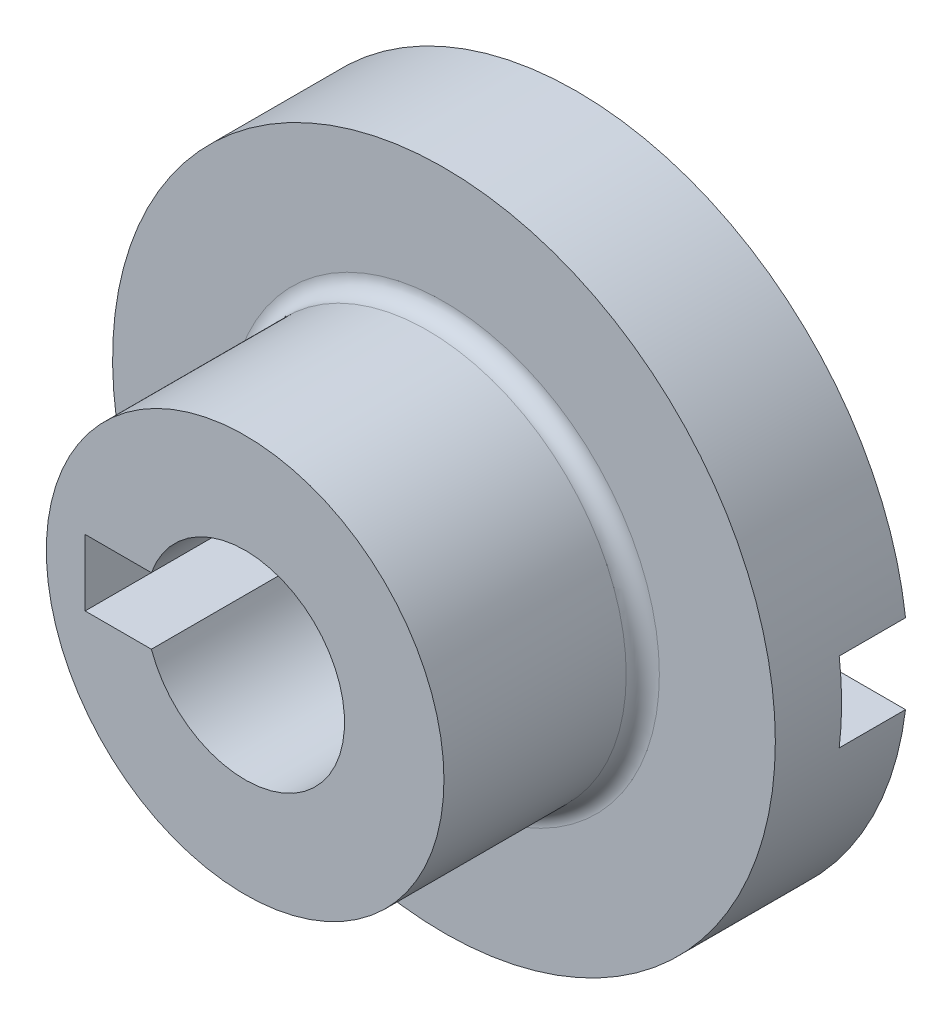
SolidWorks part; units mm, degrees
ref_plane "Front Plane" through (0, 0, 0) normal (0, 0, 1) x (1, 0, 0)
ref_plane "Top Plane" through (0, 0, 0) normal (0, 1, 0) x (1, 0, 0)
ref_plane "Right Plane" through (0, 0, 0) normal (1, 0, 0) x (0, 0, -1)
sketch "Sketch2" plane through (0, 0, 0) normal (0, 0, 1) x (1, 0, 0)
  circle A0 centre (0, 0) radius 50
  dimension "D1" = 100
extrude "Boss-Extrude1" add sketch "Sketch2" along normal blind 20
sketch "Sketch3" plane through (0, 0, 20) normal (0, 0, 1) x (1, 0, 0)
  circle A0 centre (0, 0) radius 30
  dimension "D1" = 60
extrude "Boss-Extrude2" add sketch "Sketch3" along normal blind 30
fillet "Fillet1" radius 2.5 1 edges at (30, 0, 20)
sketch "Sketch4" plane through (0, 0, 0) normal (0, 0, -1) x (-1, 0, 0)
  line L1 (-55, 6) -> (55, 6)
  line L2 (-55, 6) -> (-55, -6)
  line L3 (-55, -6) -> (55, -6)
  line L4 (55, 6) -> (55, -6)
  point P4 (55, 0)
  dimension "D1" = 12
  dimension "D2" = 110
  dimension "D3" = 55
extrude "Cut-Extrude1" cut sketch "Sketch4" against normal blind 10
sketch "Sketch5" plane through (0, 0, 50) normal (0, 0, 1) x (1, 0, 0)
  line L1 (-14.1421, 5) -> (-24.1421, 5)
  line L2 (-24.1421, 5) -> (-24.1421, -5)
  line L3 (-24.1421, -5) -> (-14.1421, -5)
  arc A0 (-14.1421, -5) -> (-14.1421, 5) centre (0, 0) ccw
  dimension "D1" = 30
  dimension "D2" = 10
  dimension "D3" = 10
  dimension "D4" = 24.1421
extrude "Cut-Extrude2" cut sketch "Sketch5" against normal up to surface (50 mm away) up to face at (0, 28, 0)
